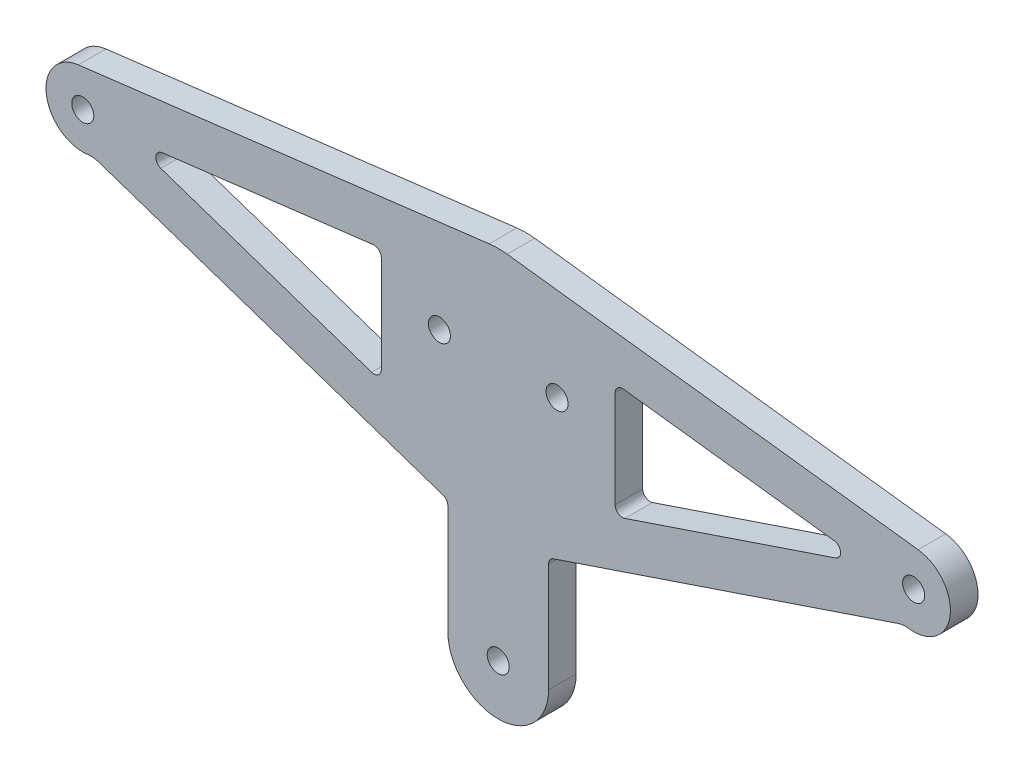
SolidWorks part; units mm, degrees
ref_plane "Plano frontal" through (0, 0, 0) normal (0, 0, 1) x (1, 0, 0)
ref_plane "Plano superior" through (0, 0, 0) normal (0, 1, 0) x (1, 0, 0)
ref_plane "Plano direito" through (0, 0, 0) normal (1, 0, 0) x (0, 0, -1)
sketch "Esboço1" plane through (0, 0, 0) normal (0, 0, 1) x (1, 0, 0)
  line L0 (0, 0) -> (113, 0) construction
  line L1 (56.5, 11.9749) -> (56.5, -43.5251) construction
  line L2 (56.5, 11.9749) -> (-0.6093, 4.9627)
  line L3 (56.5, 11.9749) -> (113.6093, 4.9627)
  line L4 (56.5, 11.9749) -> (118, 11.9749) construction
  line L5 (49.65, -36.6751) -> (49.65, -21.8431)
  line L6 (63.35, -36.6751) -> (63.35, -21.8431)
  line L7 (64.0303, -20.8956) -> (110.9129, -5.0775)
  line L8 (48.9697, -20.8956) -> (2.0871, -5.0775)
  line L9 (63.35, -21.1251) -> (111.6736, -4.8209) construction
  line L10 (39.2803, -11.2941) -> (10.6094, -1.6206)
  line L11 (73.7197, -11.2941) -> (102.3906, -1.6206)
  line L12 (73.5219, 3.8398) -> (102.1928, 0.3195)
  line L13 (40.6, 2.8472) -> (40.6, -10.3466)
  line L14 (51.5681, -15.44) -> (3.2445, 0.8643) construction
  line L15 (49.65, -21.1251) -> (1.3264, -4.8209) construction
  line L16 (55.7688, 6.0196) -> (112.8781, -0.9925) construction
  line L17 (72.4, 2.8472) -> (72.4, -10.3466)
  line L18 (61.4319, -15.44) -> (109.7555, 0.8643) construction
  line L19 (39.4781, 3.8398) -> (10.8072, 0.3195)
  circle A0 centre (0, 0) radius 1.5
  circle A1 centre (113, 0) radius 1.5
  circle A2 centre (48.5, -1.6751) radius 1.5
  circle A3 centre (64.5, -1.6751) radius 1.5
  circle A4 centre (56.5, -36.6751) radius 1.5
  arc A5 (-0.6093, 4.9627) -> (0.705, -4.95) centre (0, 0) ccw
  arc A6 (112.295, -4.95) -> (113.6093, 4.9627) centre (113, 0) ccw
  arc A7 (49.65, -36.6751) -> (63.35, -36.6751) centre (56.5, -36.6751) ccw
  arc A8 (102.1928, 0.3195) -> (102.3906, -1.6206) centre (102.0709, -0.6731) cw
  arc A9 (72.4, -10.3466) -> (73.7197, -11.2941) centre (73.4, -10.3466) ccw
  arc A10 (72.4, 2.8472) -> (73.5219, 3.8398) centre (73.4, 2.8472) cw
  arc A11 (40.6, -10.3466) -> (39.2803, -11.2941) centre (39.6, -10.3466) cw
  arc A12 (40.6, 2.8472) -> (39.4781, 3.8398) centre (39.6, 2.8472) ccw
  arc A13 (10.8072, 0.3195) -> (10.6094, -1.6206) centre (10.9291, -0.6731) ccw
  arc A14 (63.35, -21.8431) -> (64.0303, -20.8956) centre (64.35, -21.8431) cw
  arc A15 (49.65, -21.8431) -> (48.9697, -20.8956) centre (48.65, -21.8431) ccw
  arc A16 (110.9129, -5.0775) -> (112.295, -4.95) centre (111.872, -7.9201) cw
  arc A17 (2.0871, -5.0775) -> (0.705, -4.95) centre (1.128, -7.9201) ccw
  point P11 (1.5, 0)
  point P12 (111.5, 0)
  point P13 (57.2312, 6.0196)
  point P15 (63, -1.6751)
  point P19 (0.1219, -0.9925)
  point P20 (56.5, -35.1751)
  point P22 (56.5, -43.5251)
  point P24 (48.5, -3.1751)
  point P32 (50, -1.6751)
  point P54 (72.4, 3.9775)
  point P59 (40.6, 3.9775)
  point P62 (63.35, -21.1251)
  point P64 (118, 0)
  point P67 (49.65, -21.1251)
  dimension "D1" = 3
  dimension "D4" = 10
  dimension "D5" = 13.7
  dimension "D12" = 1
  dimension "D17" = 1
  dimension "D10" = 3
  dimension "D2" = 110
  dimension "D3" = 55
  dimension "D6" = 55.5
  dimension "D7" = 7
  dimension "D8" = 13
  dimension "D9" = 32
  dimension "D11" = 22.4
  dimension "D16" = 31.8
  dimension "D18" = 49.4792
  dimension "D13" = 6
  dimension "D14" = 6
  dimension "D15" = 6
extrude "Ressalto-extrusão1" add sketch "Esboço1" along normal blind 3.75
fillet "Filete2" radius 10 1 edges at (56.5, 11.9749, 1.875)
